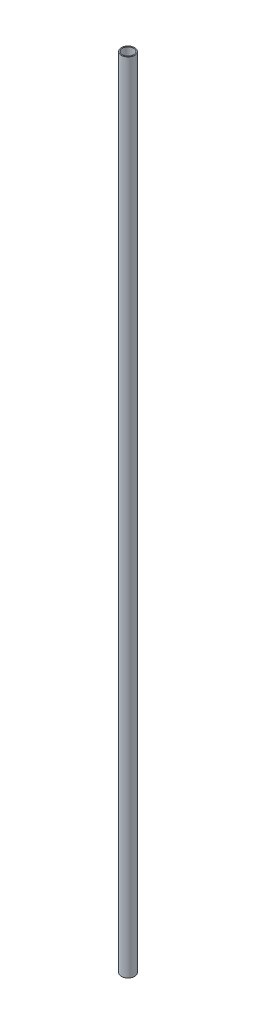
SolidWorks part; units mm, degrees
ref_plane "Front Plane" through (0, 0, 0) normal (0, 0, 1) x (1, 0, 0)
ref_plane "Top Plane" through (0, 0, 0) normal (0, 1, 0) x (1, 0, 0)
ref_plane "Right Plane" through (0, 0, 0) normal (1, 0, 0) x (0, 0, -1)
sketch "Sketch1" plane through (0, 0, 0) normal (0, 1, 0) x (1, 0, 0)
  circle A0 centre (0, 0) radius 6.45
  circle A1 centre (0, 0) radius 5.45
extrude "Boss-Extrude1" add sketch "Sketch1" along normal blind 770
